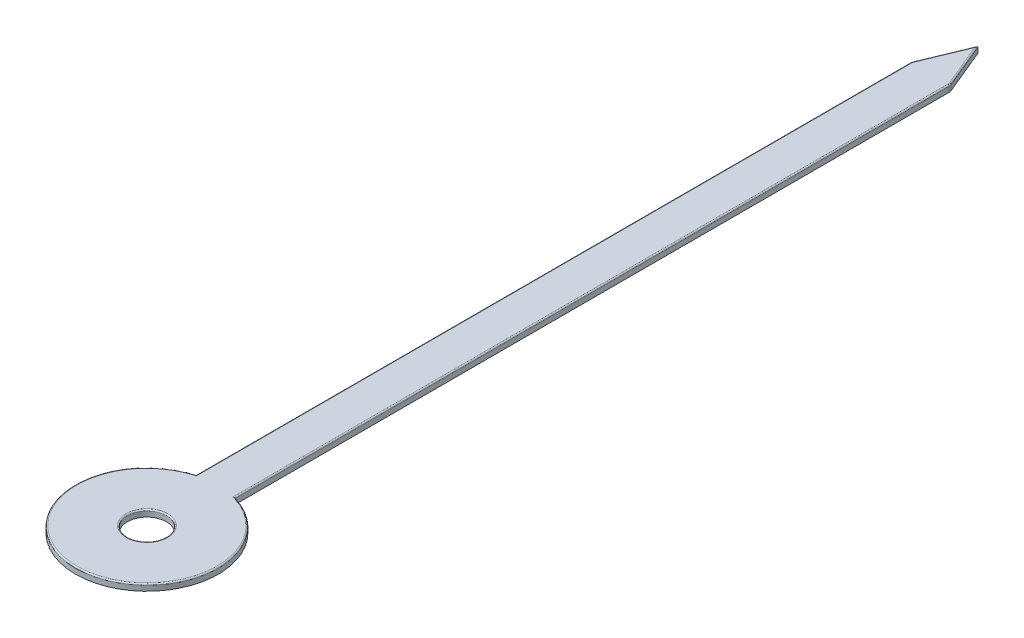
SolidWorks part; units mm, degrees
ref_plane "前视基准面" through (0, 0, 0) normal (0, 0, 1) x (1, 0, 0)
ref_plane "上视基准面" through (0, 0, 0) normal (0, 1, 0) x (1, 0, 0)
ref_plane "右视基准面" through (0, 0, 0) normal (1, 0, 0) x (0, 0, -1)
sketch "草图1" plane through (0, 0, 0) normal (0, 1, 0) x (1, 0, 0)
  line L0 (0, 0) -> (0, 12.8) construction
  line L1 (0.3, 1.0583) -> (0.3, 12.0757)
  line L2 (-0.3, 1.0583) -> (-0.3, 12.0757)
  line L3 (-0.3, 12.0757) -> (0, 12.8)
  line L4 (0, 12.8) -> (0.3, 12.0757)
  line L6 (-0.3, 0) -> (-0.3, 12.8) construction
  line L7 (0.3, 0) -> (0.3, 12.8) construction
  arc A0 (-0.3, 1.0583) -> (0.3, 1.0583) centre (0, 0) ccw
  circle A1 centre (0, 0) radius 0.3
  dimension "D1" = 2.2
  dimension "D6" = 0.6
  dimension "D2" = 12.8
  dimension "D5" = 45
  dimension "D3" = 0.3
  dimension "D4" = 0.3
extrude "凸台-拉伸1" add sketch "草图1" along normal blind 0.1
fillet "圆角1" radius 0.1 2 edges at (-0.3, 0.05, -12.0757) (0.3, 0.05, -12.0757)
fillet "圆角2" radius 0.02 8 edges at (0, 0.1, 0.3) (0.1462, 0.1, -12.4471) (0.2981, 0.1, -12.0754) (0.3, 0.1, -6.5571) (0, 0.1, 1.1) (-0.3, 0.1, -6.5571) (-0.2981, 0.1, -12.0754) (-0.1462, 0.1, -12.4471)
